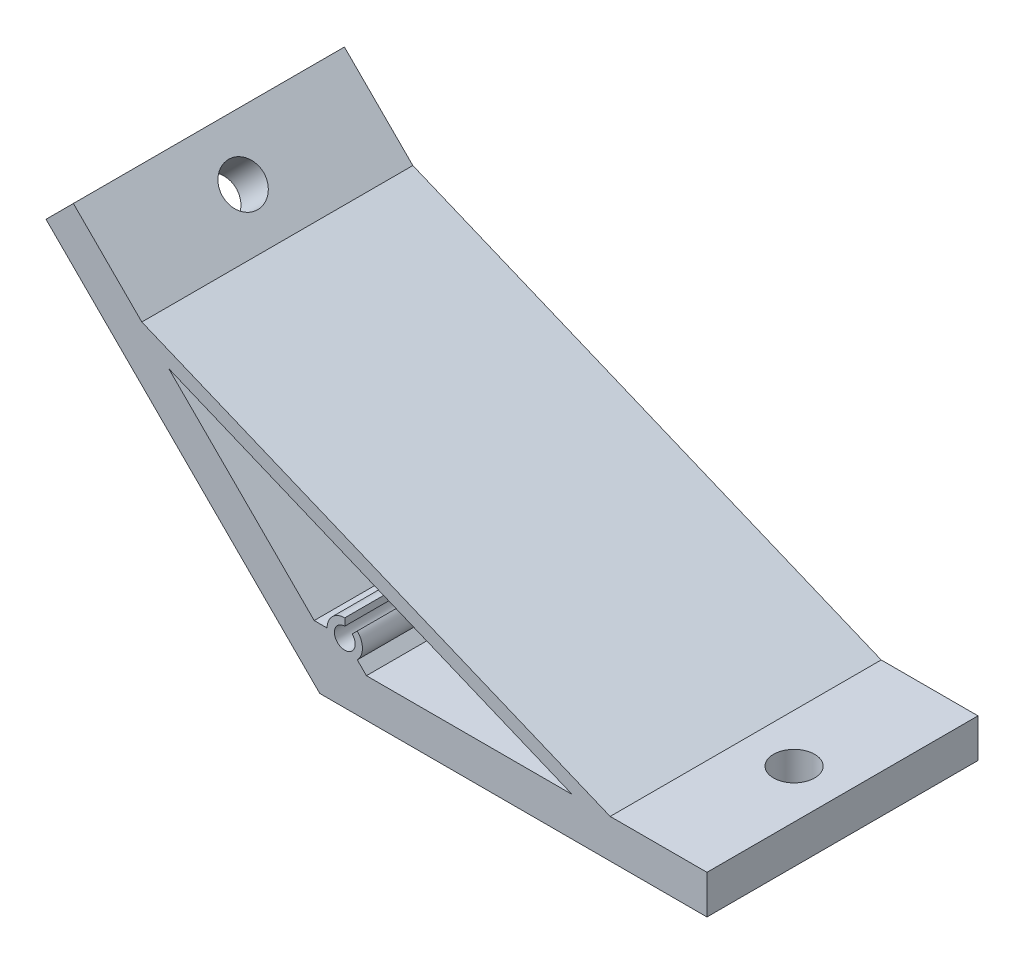
SolidWorks part; units mm, degrees
ref_plane "前视基准面" through (0, 0, 0) normal (0, 0, 1) x (1, 0, 0)
ref_plane "上视基准面" through (0, 0, 0) normal (0, 1, 0) x (1, 0, 0)
ref_plane "右视基准面" through (0, 0, 0) normal (1, 0, 0) x (0, 0, -1)
sketch "草图1" plane through (0, 0, 0) normal (0, 0, 1) x (1, 0, 0)
  line B0 (80, 0) -> (0, 0)
  line B1 (80, 8) -> (60, 8)
  line B2 (52.1606, 8) -> (9.6386, 8)
  line B3 (0, 0) -> (-56.5685, 56.5685)
  line B4 (-1.1587, 12.4724) -> (-31.2263, 42.54)
  line B5 (-36.7696, 48.0833) -> (-50.9117, 62.2254)
  line B6 (-50.9117, 62.2254) -> (-56.5685, 56.5685)
  line B7 (80, 8) -> (80, 0)
  line B8 (-1.1587, 12.4724) -> (1.5162, 12.4724)
  line B9 (9.6386, 8) -> (7.7472, 9.8914)
  line B10 (6.6865, 13.9927) -> (7.7472, 15.0533)
  line B11 (5.1662, 14.6224) -> (5.1662, 16.1224)
  line B12 (-36.7696, 48.0833) -> (60, 8)
  line B13 (-31.2263, 42.54) -> (52.1606, 8)
  arc B14 (5.1662, 14.6224) -> (6.6865, 13.9927) centre (5.1662, 12.4724) ccw
  arc B15 (7.7472, 9.8914) -> (7.7472, 15.0533) centre (5.1662, 12.4724) ccw
  arc B16 (5.1662, 16.1224) -> (1.5162, 12.4724) centre (5.1662, 12.4724) ccw
sketch_block_instance "A$C053212F5-1"
sketch_block "A$C053212F5"
extrude "凸台-拉伸1" add sketch "草图1" along normal mid plane 56
sketch "草图3" plane through (0, 8, 0) normal (0, 1, 0) x (1, 0, 0)
  line L0 (80, -28) -> (80, 28) construction
  circle A0 centre (70, 0) radius 4.25
  dimension "D1" = 10
extrude "切除-拉伸1" cut sketch "草图3" against normal through all
sketch "草图4" plane through (11.6152, 28.0416, 0) normal (0.3827, 0.9239, 0) x (0.9239, -0.3827, 0)
  line L0 (0, -28) -> (0, 28) construction
  line L1 (52.3713, -28) -> (-52.3713, -28) construction
  line L2 (52.3713, 28) -> (-52.3713, 28) construction
ref_plane "基准面2" through (0, 0, 0) normal (-0.9239, 0.3827, 0) x (0, 0, 1)
mirror "镜向1" about plane through (0, 0, 0) normal (-0.9239, 0.3827, 0) of "切除-拉伸1"
